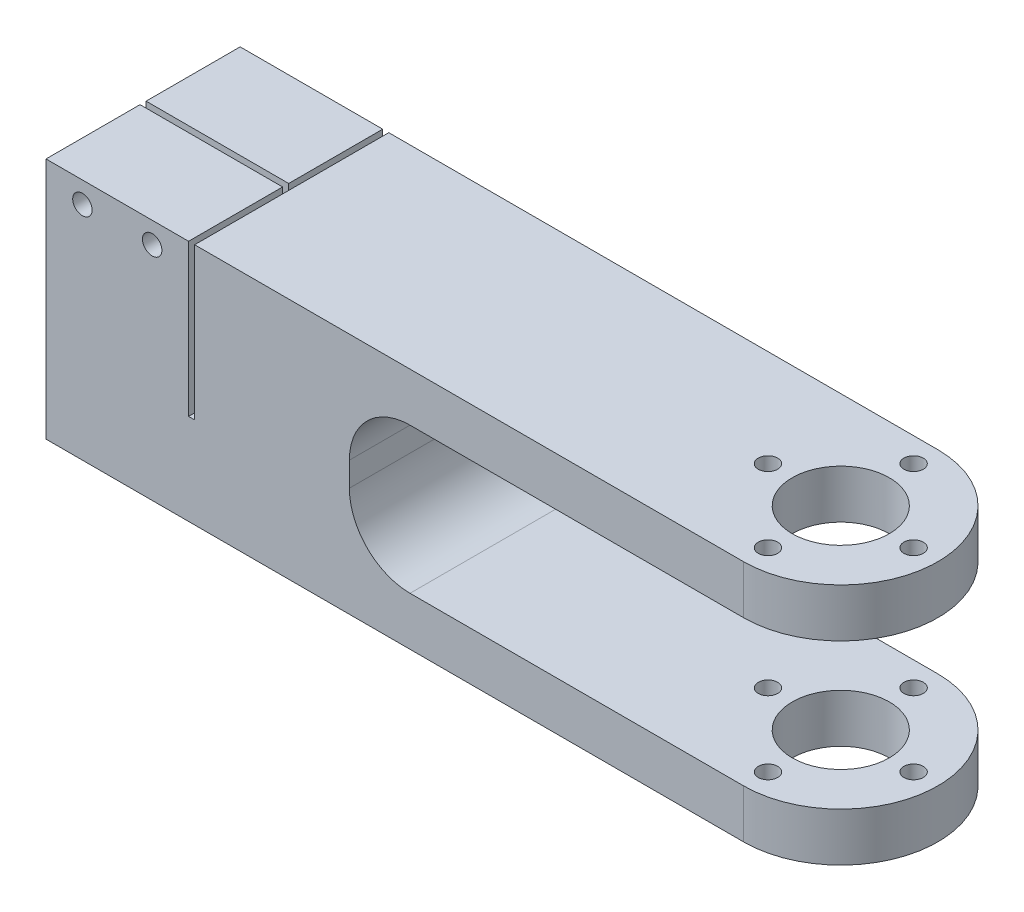
SolidWorks part; units mm, degrees
material "氧化铝"
ref_plane "前视基准面" through (0, 0, 0) normal (0, 0, 1) x (1, 0, 0)
ref_plane "上视基准面" through (0, 0, 0) normal (0, 1, 0) x (1, 0, 0)
ref_plane "右视基准面" through (0, 0, 0) normal (1, 0, 0) x (0, 0, -1)
sketch "草图1" plane through (0, 0, 0) normal (0, 1, 0) x (1, 0, 0)
  line L1 (-57.5, 16) -> (57.5, 16)
  line L2 (-57.5, 16) -> (-57.5, -16)
  line L3 (-57.5, -16) -> (57.5, -16)
  line L5 (-57.5, 16) -> (57.5, -16) construction
  line L6 (-57.5, -16) -> (57.5, 16) construction
  arc A1 (57.5, -16) -> (57.5, 16) centre (57.5, 0) ccw
  point P0 (0, 0)
  dimension "D1" = 32
  dimension "D2" = 115
extrude "凸台-拉伸1" add sketch "草图1" along normal mid plane 40
sketch "草图2" plane through (0, 20, 0) normal (0, 1, 0) x (1, 0, 0)
  circle A0 centre (57.5, 0) radius 8
  dimension "D1" = 16
extrude "切除-拉伸1" cut sketch "草图2" against normal up to next
sketch "草图4" plane through (-57.5, 0, 0) normal (-1, 0, 0) x (0, 0, 1)
  circle A0 centre (0, 0) radius 12.5
  dimension "D1" = 25
extrude "切除-拉伸2" cut sketch "草图4" against normal blind 40
sketch "草图5" plane through (0, 0, 16) normal (0, 0, 1) x (1, 0, 0)
  line L0 (73.5, -20) -> (73.5, 20) construction
  line L1 (73.5, 12) -> (-7.5, 12)
  line L2 (73.5, 12) -> (73.5, -12)
  line L3 (73.5, -12) -> (-7.5, -12)
  line L4 (-7.5, 12) -> (-7.5, -12)
  line L5 (-57.5, 20) -> (-57.5, -20) construction
  point P9 (-7.5, 0)
  dimension "D1" = 50
  dimension "D2" = 24
extrude "切除-拉伸3" cut sketch "草图5" against normal up to next
sketch "草图6" plane through (0, 20, 0) normal (0, 1, 0) x (1, 0, 0)
  line L0 (-57.5, 16) -> (-57.5, -16) construction
  line L1 (-33.5, -0.5) -> (-57.5, -0.5)
  line L2 (-33.5, -0.5) -> (-33.5, 0.5)
  line L3 (-33.5, 0.5) -> (-57.5, 0.5)
  line L4 (-57.5, -0.5) -> (-57.5, 0.5)
  line L5 (-33.5, -0.5) -> (-57.5, 0.5) construction
  line L6 (-33.5, 0.5) -> (-57.5, -0.5) construction
  point P0 (-45.5, 0)
  dimension "D1" = 1
  dimension "D2" = 12
extrude "切除-拉伸4" cut sketch "草图6" against normal up to next
sketch "草图7" plane through (0, 20, 0) normal (0, 1, 0) x (1, 0, 0)
  line L0 (-33.5, -0.5) -> (-33.5, 0.5) construction
  line L1 (-34, 16) -> (-33, 16)
  line L2 (-34, 16) -> (-34, -16)
  line L3 (-34, -16) -> (-33, -16)
  line L4 (-33, 16) -> (-33, -16)
  line L5 (-34, 16) -> (-33, -16) construction
  line L6 (-34, -16) -> (-33, 16) construction
  line L7 (-57.5, -16) -> (57.5, -16) construction
  point P0 (-33.5, 0)
  dimension "D1" = 1
extrude "切除-拉伸5" cut sketch "草图7" against normal blind 25
sketch "草图8" plane through (0, 0, 16) normal (0, 0, 1) x (1, 0, 0)
  line L0 (-57.5, 20) -> (-34, 20) construction
  line L1 (-57.5, 20) -> (-57.5, -20) construction
  line L2 (-34, -5) -> (-34, 20) construction
  circle A0 centre (-51.5, 16.5) radius 1.6
  circle A1 centre (-40, 16.5) radius 1.6
  dimension "D2" = 3.2
  dimension "D3" = 3.2
  dimension "D1" = 3.5
  dimension "D4" = 6
  dimension "D5" = 6
extrude "切除-拉伸6" cut sketch "草图8" against normal up to surface (32 mm away)
sketch "草图9" plane through (0, 20, 0) normal (0, 1, 0) x (1, 0, 0)
  circle A0 centre (57.5, 0) radius 12 construction
  circle A1 centre (69.5, 0) radius 1.6
  circle A2 centre (45.5, 0) radius 1.6
  circle A3 centre (57.5, 12) radius 1.6
  circle A4 centre (57.5, -12) radius 1.6
  dimension "D1" = 24
  dimension "D2" = 3.2
  dimension "D3" = 3.2
  dimension "D4" = 3.2
  dimension "D5" = 3.2
extrude "切除-拉伸7" cut sketch "草图9" against normal through all
fillet "圆角1" radius 10 2 edges at (-7.5, -12, 0) (-7.5, 12, 0)
